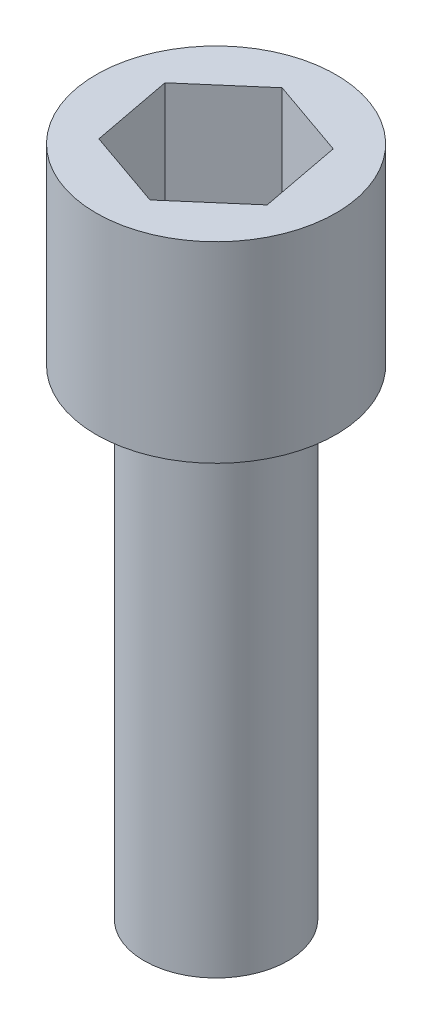
SolidWorks part; units mm, degrees
ref_plane "Plan de face" through (0, 0, 0) normal (0, 0, 1) x (1, 0, 0)
ref_plane "Plan de dessus" through (0, 0, 0) normal (0, 1, 0) x (1, 0, 0)
ref_plane "Plan de droite" through (0, 0, 0) normal (1, 0, 0) x (0, 0, -1)
sketch "Esquisse1" plane through (0, 0, 0) normal (0, 1, 0) x (1, 0, 0)
  circle A0 centre (0, 0) radius 3
extrude "Boss.-Extru.2" add sketch "Esquisse1" along normal blind 20
sketch "Esquisse4" plane through (0, 20, 0) normal (0, 1, 0) x (1, 0, 0)
  circle A0 centre (0, 0) radius 5
extrude "Boss.-Extru.5" add sketch "Esquisse4" along normal blind 8
sketch "Esquisse6" plane through (0, 28, 0) normal (0, 1, 0) x (1, 0, 0)
  line L1 (0.648, -3.403) -> (3.271, -1.1403)
  line L2 (3.271, -1.1403) -> (2.6231, 2.2626)
  line L3 (2.6231, 2.2626) -> (-0.648, 3.403)
  line L4 (-0.648, 3.403) -> (-3.271, 1.1403)
  line L5 (-3.271, 1.1403) -> (-2.6231, -2.2626)
  line L6 (-2.6231, -2.2626) -> (0.648, -3.403)
  circle A0 centre (0, 0) radius 3 construction
extrude "Enlèv. mat.-Extru.3" cut sketch "Esquisse6" against normal blind 5
